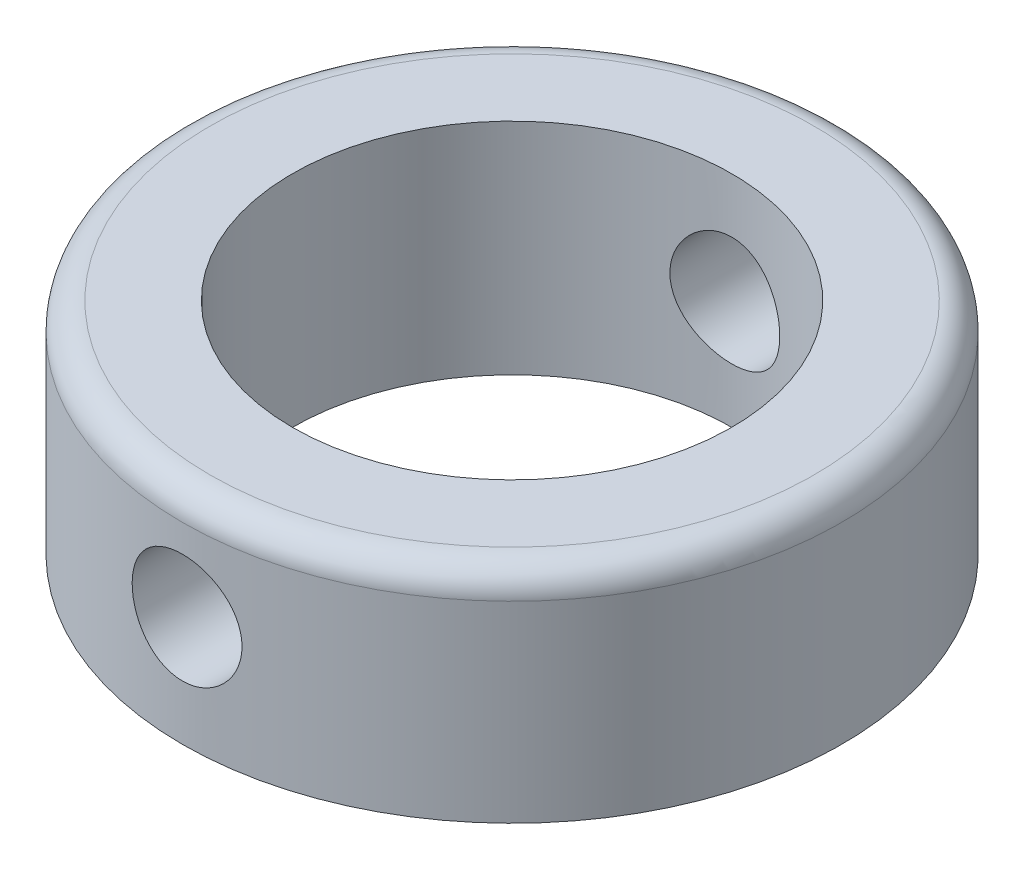
SolidWorks part; units mm, degrees
ref_plane "Front Plane" through (0, 0, 0) normal (0, 0, 1) x (1, 0, 0)
ref_plane "Top Plane" through (0, 0, 0) normal (0, 1, 0) x (1, 0, 0)
ref_plane "Right Plane" through (0, 0, 0) normal (1, 0, 0) x (0, 0, -1)
sketch "Sketch1" plane through (0, 0, 0) normal (0, 1, 0) x (1, 0, 0)
  circle A0 centre (0, 0) radius 12
  circle A1 centre (0, 0) radius 8
  dimension "D1" = 16
  dimension "D2" = 24
extrude "Boss-Extrude1" add sketch "Sketch1" along normal mid plane 8
fillet "Fillet1" radius 1 1 edges at (0, 4, 12)
sketch "Sketch2" plane through (0, 0, 0) normal (0, 0, 1) x (1, 0, 0)
  circle A0 centre (0, 0) radius 2
  dimension "D1" = 4
extrude "Cut-Extrude1" cut sketch "Sketch2" against normal mid plane 38
